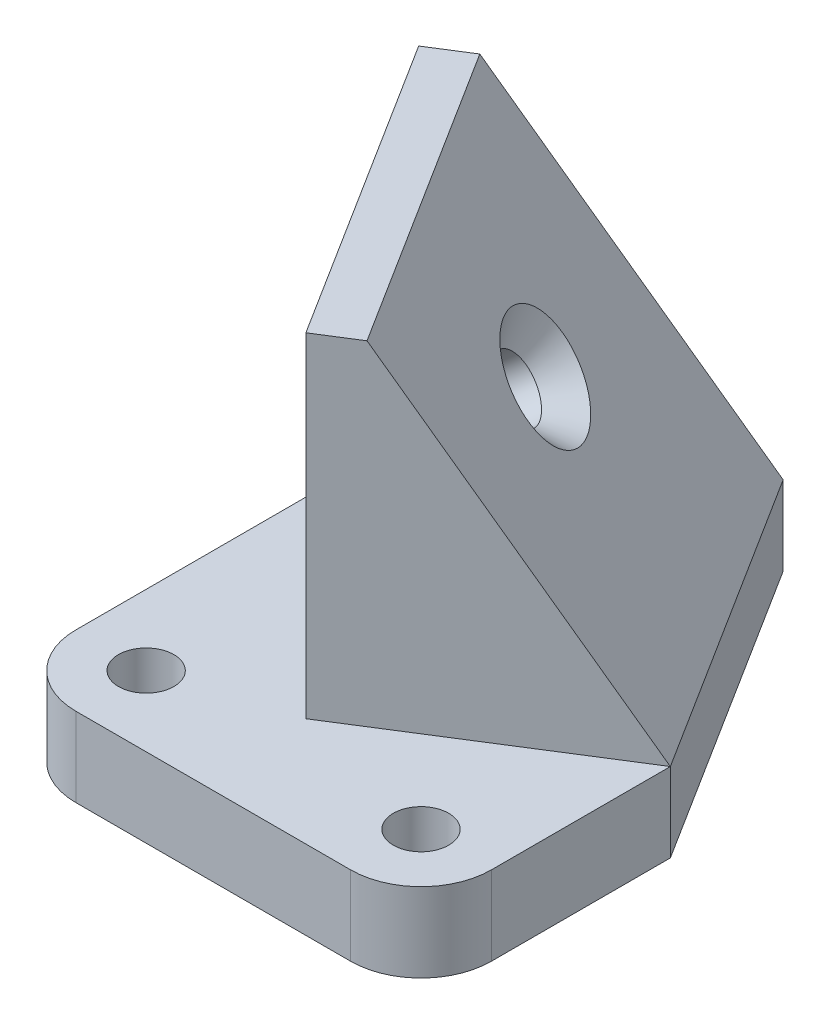
SolidWorks part; units mm, degrees
ref_plane "Front" through (0, 0, 0) normal (0, 0, 1) x (1, 0, 0)
ref_plane "Top" through (0, 0, 0) normal (0, 1, 0) x (1, 0, 0)
ref_plane "Right" through (0, 0, 0) normal (1, 0, 0) x (0, 0, -1)
sketch "Sketch1" plane through (0, 0, 0) normal (0, 1, 0) x (1, 0, 0)
  line L0 (0, 0) -> (0, 45)
  line L1 (0, 45) -> (-34.641, 100)
  line L2 (0, 0) -> (-75, 0)
  line L3 (-75, 0) -> (-75, 74.5804)
  line L4 (-34.641, 100) -> (-75, 74.5804)
  dimension "D1" = 75
  dimension "D2" = 45
  dimension "D3" = 32.204
  dimension "D5" = 100
extrude "Base-Extrude" add sketch "Sketch1" along normal blind 14.2875
sketch "Sketch2" plane through (0, 14.2875, 0) normal (0, 1, 0) x (-1, 0, 0)
  line L0 (34.641, -100) -> (75, -74.5804)
  line L1 (75, -74.5804) -> (40.359, -19.5804)
  line L2 (34.641, -100) -> (0, -45)
  line L3 (0, -45) -> (40.359, -19.5804)
extrude "Boss-Extrude1" add sketch "Sketch2" along normal blind 60.325
sketch "Sketch3" plane through (-20.2927, 0, -32.2189) normal (0.5329, 0, 0.8462) x (0.8462, 0, -0.5329)
  line L0 (-15.7147, 74.6125) -> (23.9822, 14.2875)
  line L1 (23.9822, 74.6125) -> (-23.7147, 74.6125) construction
  line L2 (-23.7147, 74.6125) -> (-23.7147, 14.2875) construction
  dimension "D1" = 8
extrude "Cut-Extrude1" cut sketch "Sketch3" against normal through all
hole_wizard "CSK for M10 Flat Head Machine Screw1" positions "Sketch6" profile "Sketch5" countersink size "M10" standard "Ansi Metric"
sketch "Sketch6" plane through (19.7121, 15.3301, -12.4154) normal (0.7068, 0.5497, -0.4452) x (-0.3678, -0.252, -0.8951)
  line L0 (98.6509, 29.9065) -> (76.8651, 98.7566) construction
  line L1 (14.8935, 79.1473) -> (76.8651, 98.7566) construction
  point P0 (53.6091, 60.4335)
  dimension "D1" = 33.7338
  dimension "D2" = 29.5216
sketch "Sketch5" plane through (-36.5211, 49.9514, -58.9486) normal (-0.104, 0.7033, 0.7033) x (-0.6997, 0.4508, -0.5543)
  line L0 (0, 0) -> (0, 28.7047)
  line L1 (0, 28.7047) -> (5.5, 25.4)
  line L2 (5.5, 25.4) -> (5.5, 4.5)
  line L3 (5.5, 4.5) -> (10, 0)
  line L5 (10, 0) -> (0, 0)
  line L6 (-5.5, 4.5) -> (-10, 0) construction
  line L10 (0, 28.7047) -> (-5.5, 25.4) construction
  line L11 (0, -6.35) -> (0, 107.95) construction
  dimension "Hole Dia." = 11
  dimension "Hole Depth" = 25.4
  dimension "Near C'Sink Dia." = 20
  dimension "Near C'Sink Angle" = 90
  dimension "Drill Angle" = 118
fillet "Fillet1" radius 12.7 2 edges at (0, 7.1437, 0) (-75, 7.1437, 0)
hole_wizard "Ø10.0 (10) Diameter Hole1" positions "Sketch9" profile "Sketch8" hole size "Ø10.0" standard "Ansi Metric" end condition through all
sketch "Sketch9" plane through (0, 14.2875, 0) normal (0, 1, 0) x (-1, 0, 0)
  point P0 (12.7, -12.7)
  point P1 (62.3, -12.7)
sketch "Sketch8" plane through (-12.7, 14.2875, -12.7) normal (1, 0, 0) x (0, 0, 1)
  line L0 (0, 0) -> (0, 14.2875)
  line L1 (0, 14.2875) -> (5, 14.2875)
  line L2 (5, 14.2875) -> (5, 0)
  line L5 (5, 0) -> (0, 0)
  line L11 (0, -6.35) -> (0, 28.9116) construction
  dimension "Thru Hole Dia." = 10
  dimension "Thru Hole Depth" = 14.2875
